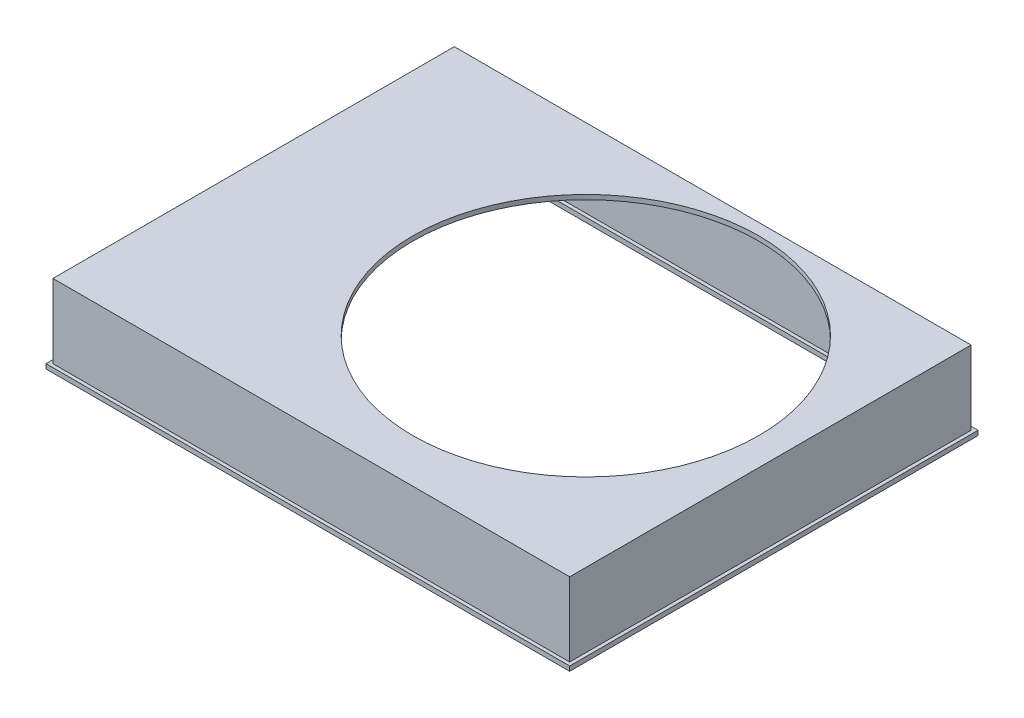
SolidWorks part; units mm, degrees
ref_plane "前视基准面" through (0, 0, 0) normal (0, 0, 1) x (1, 0, 0)
ref_plane "上视基准面" through (0, 0, 0) normal (0, 1, 0) x (1, 0, 0)
ref_plane "右视基准面" through (0, 0, 0) normal (1, 0, 0) x (0, 0, -1)
other "Configuration Table"
sketch "草图1" plane through (0, 0, 0) normal (0, 1, 0) x (1, 0, 0)
  line L1 (0, 0) -> (220, 0)
  line L2 (0, 0) -> (0, -170)
  line L3 (0, -170) -> (220, -170)
  line L4 (220, 0) -> (220, -170)
  line L9 (-2, 2) -> (222, 2)
  line L10 (-2, 2) -> (-2, -172)
  line L11 (-2, -172) -> (222, -172)
  line L12 (222, 2) -> (222, -172)
  point P4 (-2, 0)
  point P5 (0, 2)
  point P7 (222, -170)
  point P8 (220, -172)
  dimension "D1" = 220
  dimension "D2" = 170
  dimension "D3" = 2
  dimension "D4" = 2
  dimension "D5" = 2
  dimension "D6" = 2
extrude "凸台-拉伸1" add sketch "草图1" along normal blind 32
sketch "草图2" plane through (0, 0, 0) normal (0, 1, 0) x (1, 0, 0)
  line L0 (220, -170) -> (220, 0) construction
  line L1 (0, -170) -> (220, -170) construction
  line L2 (0, 0) -> (0, -170) construction
  line L3 (220, 0) -> (0, 0) construction
  line L14 (-3.5, 3.5) -> (223.5, 3.5)
  line L15 (-3.5, 3.5) -> (-3.5, -173.5)
  line L16 (-3.5, -173.5) -> (223.5, -173.5)
  line L17 (223.5, 3.5) -> (223.5, -173.5)
  line L18 (218.5, -168.5) -> (1.5, -168.5)
  line L19 (218.5, -168.5) -> (218.5, -1.5)
  line L20 (218.5, -1.5) -> (1.5, -1.5)
  line L21 (1.5, -168.5) -> (1.5, -1.5)
  point P0 (-3.5, 2)
  point P1 (-2, 3.5)
  point P2 (222, -173.5)
  point P3 (223.5, -172)
  point P4 (220, -168.5)
  point P5 (218.5, -170)
  point P8 (0, -1.5)
  point P11 (1.5, 0)
  point P14 (0, 0)
  point P17 (220, -170)
  point P18 (-2, 2)
  point P19 (222, -172)
  dimension "D1" = 1.5
  dimension "D2" = 1.5
  dimension "D3" = 1.5
  dimension "D4" = 1.5
  dimension "D5" = 1.5
  dimension "D6" = 1.5
  dimension "D7" = 1.5
  dimension "D8" = 1.5
extrude "凸台-拉伸2" add sketch "草图2" against normal blind 2
ref_plane "基准面1" through (0, 32, 0) normal (0, 1, 0) x (1, 0, 0)
sketch "草图3" plane through (0, 32, 0) normal (0, 1, 0) x (1, 0, 0)
  line L0 (-2, 2) -> (-2, -172) construction
  line L1 (222, -172) -> (222, 2) construction
  line L7 (-2, 2) -> (220, 2)
  line L8 (-2, 2) -> (-2, -170)
  line L9 (-2, -170) -> (220, -170)
  line L10 (220, 2) -> (220, -170)
  circle A0 centre (135, -78) radius 75
  point P0 (-2, -78)
  point P1 (222, -78)
  point P5 (210, -78)
  point P8 (60, -78)
  point P9 (135, -78)
  dimension "D1" = 80
  dimension "D2" = 12
  dimension "D3" = 62
  dimension "D4" = 75
extrude "凸台-拉伸3" add sketch "草图3" against normal blind 2
